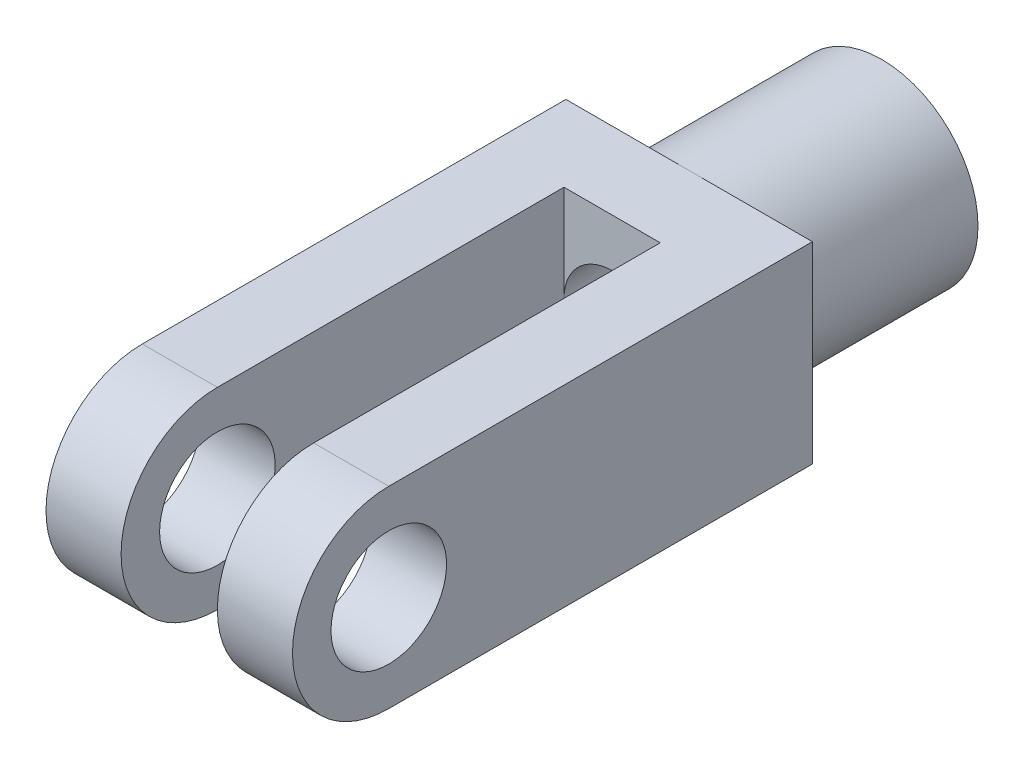
SolidWorks part; units mm, degrees
ref_plane "前视基准面" through (0, 0, 0) normal (0, 0, 1) x (1, 0, 0)
ref_plane "上视基准面" through (0, 0, 0) normal (0, 1, 0) x (1, 0, 0)
ref_plane "右视基准面" through (0, 0, 0) normal (1, 0, 0) x (0, 0, -1)
sketch "Sketch1" plane through (0, 0, 0) normal (0, 0, 1) x (1, 0, 0)
  circle A0 centre (0, 0) radius 2.5
  circle A1 centre (0, 0) radius 1.5
  dimension "D1" = 3
  dimension "D2" = 5
extrude "Boss-Extrude1" add sketch "Sketch1" along normal blind 5
sketch "Sketch2" plane through (0, 0, 5) normal (0, 0, 1) x (1, 0, 0)
  line L0 (0, 3.9295) -> (0, -4.311) construction
  line L1 (3.2, 2.5) -> (-3.2, 2.5)
  line L2 (-3.2, 2.5) -> (-3.2, -2.5)
  line L3 (3.2, 2.5) -> (3.2, -2.5)
  line L4 (-5, 0) -> (0, 0) construction
  line L5 (3.2, -2.5) -> (-3.2, -2.5)
  circle A0 centre (0, 0) radius 2.5 construction
  point P10 (0, 2.5)
  point P13 (0, -2.5)
  point P15 (2.5, 0)
  point P16 (-2.5, 0)
  dimension "D1" = 6.4
  dimension "D2" = 2.5
extrude "Boss-Extrude2" add sketch "Sketch2" along normal blind 13.5
sketch "Sketch3" plane through (0, 0, 18.5) normal (0, 0, 1) x (1, 0, 0)
  line L0 (0, 3.5798) -> (0, -3.122) construction
  line L1 (-1.25, 2.5) -> (1.25, 2.5)
  line L2 (3.2, 2.5) -> (-3.2, 2.5) construction
  line L3 (-1.25, 2.5) -> (-1.25, -2.5)
  line L4 (-3.2, -2.5) -> (3.2, -2.5) construction
  line L5 (-1.25, -2.5) -> (1.25, -2.5)
  line L6 (1.25, 2.5) -> (1.25, -2.5)
  point P12 (0, -2.5)
  point P13 (0, 2.5)
  dimension "D1" = 2.5
extrude "Cut-Extrude1" cut sketch "Sketch3" against normal blind 11.5
sketch "Sketch4" plane through (-3.2, 0, 0) normal (-1, 0, 0) x (0, 0, 1)
  line L0 (18.5, 2.5) -> (18.5, -2.5) construction
  line L1 (18.5, 2.5) -> (5, 2.5) construction
  line L2 (16, 2.5) -> (20, 2.5)
  line L3 (20, 2.5) -> (20, -2.5)
  line L4 (20, -2.5) -> (16, -2.5)
  arc A0 (16, -2.5) -> (16, 2.5) centre (16, 0) ccw
  circle A1 centre (16, 0) radius 1.5
  dimension "D1" = 3
  dimension "D2" = 4
extrude "Cut-Extrude2" cut sketch "Sketch4" against normal blind 7
sketch "草图2" plane through (0, 0, 5) normal (0, 0, -1) x (-1, 0, 0)
  circle A0 centre (0, 0) radius 1.25
  dimension "D1" = 2.5
extrude "切除-拉伸1" cut sketch "草图2" against normal blind 10
